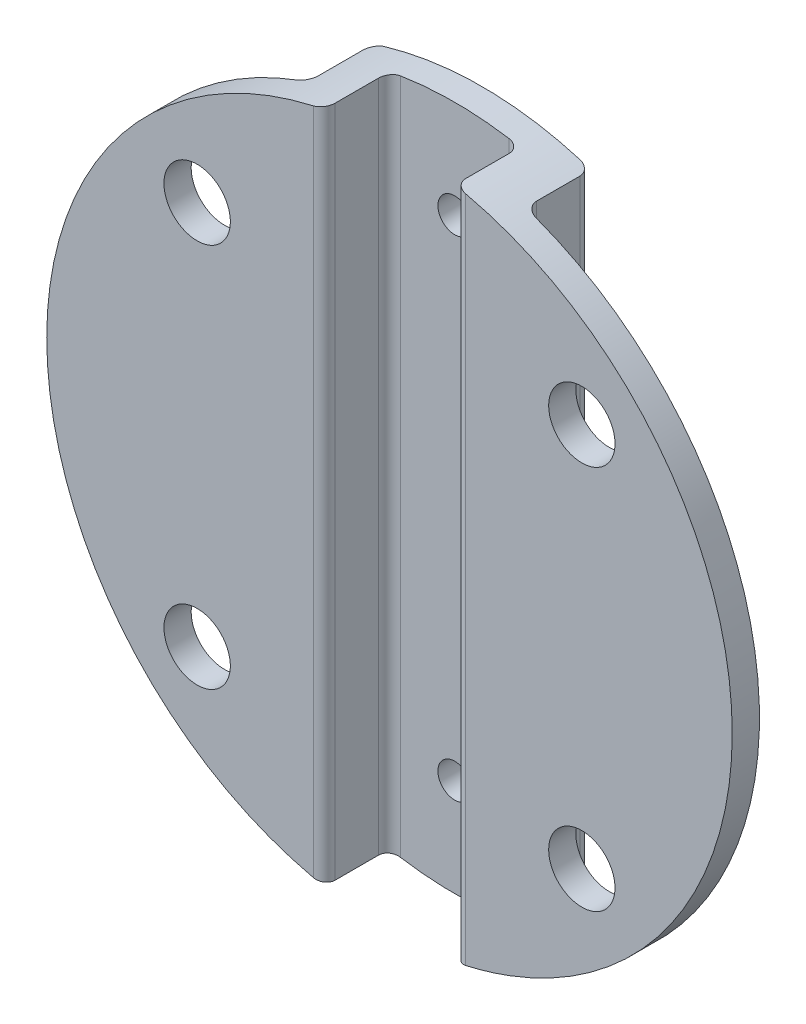
SolidWorks part; units mm, degrees
ref_plane "前视基准面" through (0, 0, 0) normal (0, 0, 1) x (1, 0, 0)
ref_plane "上视基准面" through (0, 0, 0) normal (0, 1, 0) x (1, 0, 0)
ref_plane "右视基准面" through (0, 0, 0) normal (1, 0, 0) x (0, 0, -1)
sketch "草图1" plane through (0, 0, 0) normal (0, 1, 0) x (1, 0, 0)
  line L0 (-32, 0) -> (-7, 0)
  line L1 (-6, 1) -> (-6, 5)
  line L2 (-5, 6) -> (5, 6)
  line L3 (6, 5) -> (6, 1)
  line L4 (7, 0) -> (32, 0)
  line L5 (32, 0) -> (32, 2.5)
  line L6 (32, 2.5) -> (11, 2.5)
  line L7 (10, 3.5) -> (10, 7.5)
  line L8 (9, 8.5) -> (-9, 8.5)
  line L9 (-10, 7.5) -> (-10, 3.5)
  line L10 (-11, 2.5) -> (-32, 2.5)
  line L11 (-32, 2.5) -> (-32, 0)
  arc A0 (10, 7.5) -> (9, 8.5) centre (9, 7.5) ccw
  arc A1 (11, 2.5) -> (10, 3.5) centre (11, 3.5) cw
  arc A2 (6, 1) -> (7, 0) centre (7, 1) ccw
  arc A3 (5, 6) -> (6, 5) centre (5, 5) cw
  arc A4 (-6, 5) -> (-5, 6) centre (-5, 5) cw
  arc A5 (-7, 0) -> (-6, 1) centre (-7, 1) ccw
  arc A6 (-9, 8.5) -> (-10, 7.5) centre (-9, 7.5) ccw
  arc A7 (-10, 3.5) -> (-11, 2.5) centre (-11, 3.5) cw
  point P21 (6, 6)
  point P28 (-10, 8.5)
  point P31 (-10, 2.5)
  dimension "D9" = 1
  dimension "D1" = 6
  dimension "D2" = 6
  dimension "D3" = 2.5
  dimension "D4" = 2.5
  dimension "D5" = 4
  dimension "D6" = 4
  dimension "D7" = 32
  dimension "D8" = 32
  dimension "D10" = 6
extrude "凸台-拉伸1" add sketch "草图1" along normal blind 64
sketch "草图2" plane through (0, 0, 0) normal (0, 0, 1) x (1, 0, 0)
  line L0 (-32, 64) -> (-32, 0) construction
  line L2 (-36.5571, 66.5883) -> (36.5571, 66.5883)
  line L3 (-36.5571, 66.5883) -> (-36.5571, -2.5883)
  line L4 (-36.5571, -2.5883) -> (36.5571, -2.5883)
  line L5 (36.5571, 66.5883) -> (36.5571, -2.5883)
  line L6 (-36.5571, 66.5883) -> (36.5571, -2.5883) construction
  line L7 (-36.5571, -2.5883) -> (36.5571, 66.5883) construction
  circle A0 centre (0, 32) radius 31.5
  point P2 (-32, 32)
  dimension "D1" = 63
extrude "切除-拉伸2" cut sketch "草图2" against normal blind 64
sketch "草图3" plane through (0, 0, -2.5) normal (0, 0, -1) x (-1, 0, 0)
  line L0 (-17.6777, 14.3223) -> (0, 32) construction
  line L1 (0, 32) -> (0, 0.5) construction
  circle A0 centre (-17.6777, 14.3223) radius 3.05
  arc A2 (11, 2.4831) -> (11, 61.5169) centre (0, 32) ccw construction
  arc A3 (-9, 1.8131) -> (9, 1.8131) centre (0, 32) ccw construction
  circle A4 centre (-17.6777, 49.6777) radius 3.05
  circle A5 centre (17.6777, 49.6777) radius 3.05
  circle A6 centre (17.6777, 14.3223) radius 3.05
  point P2 (0, 32)
  point P20 (0, 32)
  dimension "D2" = 6.1
  dimension "D1" = 45
  dimension "D3" = 4
  dimension "25" = 25
extrude "切除-拉伸3" cut sketch "草图3" against normal blind 64
sketch "草图4" plane through (0, 0, -8.5) normal (0, 0, -1) x (-1, 0, 0)
  arc A0 (11, 2.4831) -> (11, 61.5169) centre (0, 32) ccw construction
  circle A1 centre (0, 54.5) radius 1.55
  circle A2 centre (0, 9.5) radius 1.55
  point P0 (0, 32)
  dimension "D1" = 3.1
  dimension "3.1" = 3.1
  dimension "D2" = 22.5
  dimension "22." = 22.5
extrude "切除-拉伸4" cut sketch "草图4" against normal blind 64
ref_point "Point1"
